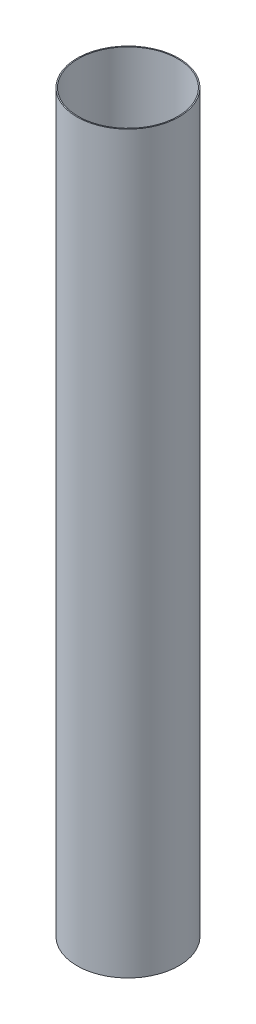
SolidWorks part; units mm, degrees
material "6061-T6 (SS)"
ref_plane "Front Plane" through (0, 0, 0) normal (0, 0, 1) x (1, 0, 0)
ref_plane "Top Plane" through (0, 0, 0) normal (0, 1, 0) x (1, 0, 0)
ref_plane "Right Plane" through (0, 0, 0) normal (1, 0, 0) x (0, 0, -1)
sketch "Sketch5" plane through (0, 0, 0) normal (0, 1, 0) x (1, 0, 0)
  circle A0 centre (0, 0) radius 49.276
  circle A1 centre (0, 0) radius 48.26
  dimension "D1" = 98.552
  dimension "D2" = 96.52
extrude "Boss-Extrude1" add sketch "Sketch5" against normal blind 711.2
